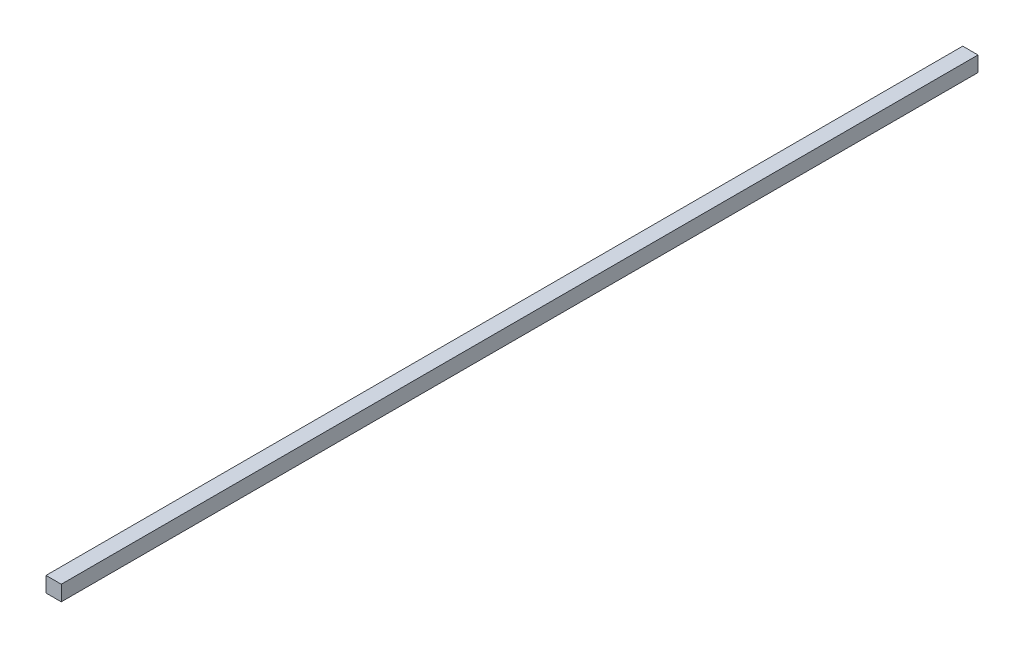
SolidWorks part; units mm, degrees
ref_plane "Front Plane" through (0, 0, 0) normal (0, 0, 1) x (1, 0, 0)
ref_plane "Top Plane" through (0, 0, 0) normal (0, 1, 0) x (1, 0, 0)
ref_plane "Right Plane" through (0, 0, 0) normal (1, 0, 0) x (0, 0, -1)
sketch "Sketch1" plane through (0, 0, 0) normal (0, 0, 1) x (1, 0, 0)
  line L1 (0, 0) -> (-25.4, 0)
  line L2 (0, 0) -> (0, 25.4)
  line L3 (0, 25.4) -> (-25.4, 25.4)
  line L4 (-25.4, 0) -> (-25.4, 25.4)
  dimension "D1" = 25.4
  dimension "D2" = 25.4
extrude "Boss-Extrude1" add sketch "Sketch1" along normal blind 1524
